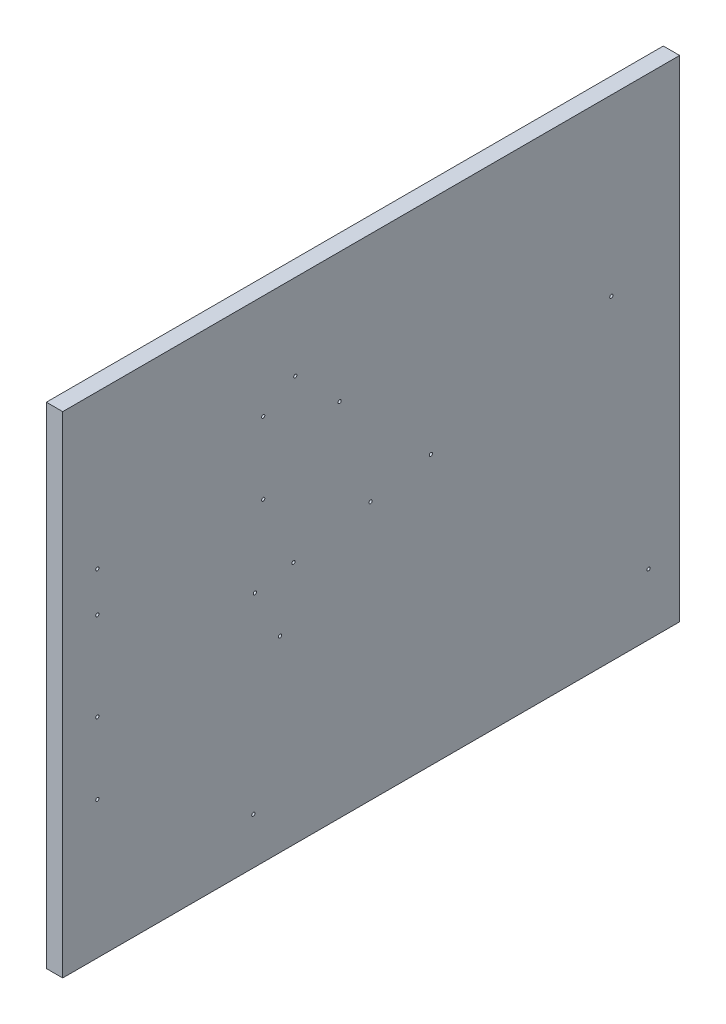
SolidWorks part; units mm, degrees
ref_plane "Спереди" through (0, 0, 0) normal (0, 0, 1) x (1, 0, 0)
ref_plane "Сверху" through (0, 0, 0) normal (0, 1, 0) x (1, 0, 0)
ref_plane "Справа" through (0, 0, 0) normal (1, 0, 0) x (0, 0, -1)
sketch "Эскиз1" plane through (0, 0, 0) normal (1, 0, 0) x (0, 0, -1)
  line L1 (-74.5221, 423.7162) -> (491.4832, 423.7162)
  line L2 (-74.5221, 423.7162) -> (-74.5221, -26.2838)
  line L3 (-74.5221, -26.2838) -> (491.4832, -26.2838)
  line L4 (491.4832, 423.7162) -> (491.4832, -26.2838)
  dimension "D1" = 566.0053
  dimension "D2" = 450
extrude "Бобышка-Вытянуть1" add sketch "Эскиз1" along normal blind 15
sketch "Эскиз3" plane through (0, 0, 0) normal (-1, 0, 0) x (0, 0, 1)
  circle A0 centre (-459.1211, 408.987) radius 4
extrude "Вырез-Вытянуть1" cut sketch "Эскиз3" against normal blind 10
sketch "Эскиз4" plane through (0, 0, 0) normal (-1, 0, 0) x (0, 0, 1)
  line L0 (-491.4832, 345.2356) -> (71.2158, 345.2356) construction
  line L1 (-491.4832, -26.2838) -> (-491.4832, 423.7162) construction
  line L2 (-208.4806, 423.7162) -> (-208.4806, -26.2838) construction
  line L3 (-491.4832, 423.7162) -> (74.5221, 423.7162) construction
  line L4 (74.5221, -26.2838) -> (-491.4832, -26.2838) construction
  line L5 (-138.8455, 423.7162) -> (-138.9099, 345.2356) construction
  line L6 (-138.9099, 345.2356) -> (-263.2761, 220.8694) construction
  line L7 (-179.4956, 423.7162) -> (-179.4956, 304.6499) construction
  line L8 (-263.2761, 220.8694) -> (-263.2761, 423.7162) construction
  line L9 (-263.2761, 220.8694) -> (-432.2169, 51.9286) construction
  line L10 (-273.2861, 210.8594) -> (74.5221, 210.8594) construction
  line L11 (-207.9311, 210.8594) -> (74.5221, 159.4945) construction
  line L12 (74.5221, 423.7162) -> (74.5221, -26.2838) construction
  line L13 (-137.1199, 197.9822) -> (-137.1199, 210.8594) construction
  line L14 (42.7147, 165.2788) -> (42.7147, 210.8594) construction
  line L15 (-207.9311, 210.8594) -> (-263.2298, 220.9157) construction
  line L16 (42.7147, 165.2788) -> (-124.8312, 145.7156) construction
  line L17 (-124.8312, 145.7156) -> (42.7147, 99.6926) construction
  line L18 (42.7147, 99.6926) -> (-100.411, 16.3608) construction
  line L19 (-101.7897, 191.5573) -> (-101.7897, 210.8594) construction
  line L20 (-101.7897, 191.5573) -> (42.7147, 246.3014) construction
  line L21 (42.7147, 246.3014) -> (-428.8213, 263.704) construction
  line L22 (-428.8213, 263.704) -> (42.7147, 282.8725) construction
  line L23 (42.7147, 282.8725) -> (-109.4447, 262.0616) construction
  line L24 (-109.4447, 262.0616) -> (-109.4447, 327.9748) construction
  line L25 (-109.4447, 327.9748) -> (66.9272, 331.7313) construction
  line L26 (-432.2169, 51.9286) -> (-463.0129, 29.9661) construction
  circle A0 centre (-138.9099, 345.2356) radius 1.5
  circle A1 centre (-179.4956, 304.6499) radius 1.5
  circle A2 centre (-263.2761, 220.8694) radius 1.5
  circle A3 centre (-207.9311, 210.8594) radius 1.5
  circle A4 centre (-137.1199, 197.9822) radius 1.5
  circle A5 centre (42.7147, 165.2788) radius 1.5
  circle A6 centre (-124.8312, 145.7156) radius 1.5
  circle A7 centre (42.7147, 99.6926) radius 1.5
  circle A8 centre (-100.411, 16.3608) radius 1.5
  circle A9 centre (-101.7897, 191.5573) radius 1.5
  circle A10 centre (42.7147, 246.3014) radius 1.5
  circle A11 centre (-428.8213, 263.704) radius 1.5
  circle A12 centre (42.7147, 282.8725) radius 1.5
  circle A13 centre (-109.4447, 262.0616) radius 1.5
  circle A14 centre (-109.4447, 327.9748) radius 1.5
  circle A15 centre (-463.0129, 29.9661) radius 1.5
  point P57 (-463.0129, 29.65)
extrude "Вырез-Вытянуть2" cut sketch "Эскиз4" against normal through all and the other way through all contours A0 | A1 | A2 | A3 | A4 | A5 | A6 | A7 | A8 | A9 | A10 | A12 | A11 | A13 | A14 | A15
